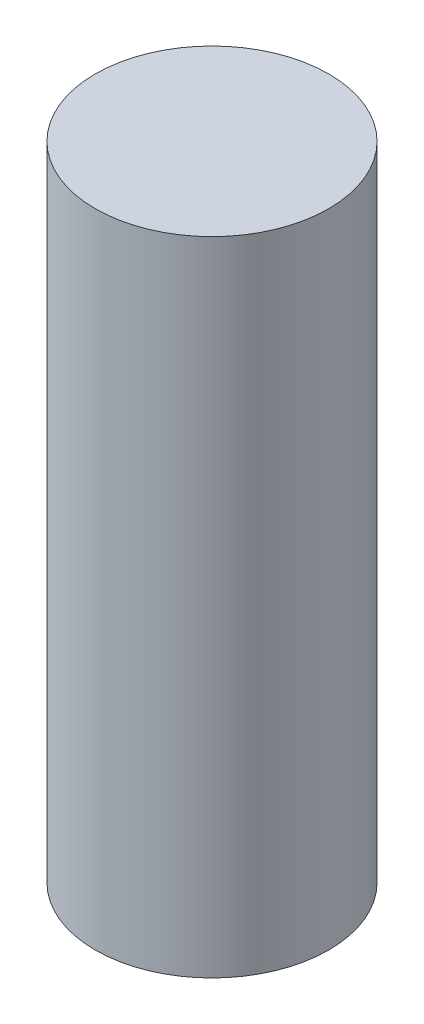
SolidWorks part; units mm, degrees
material "AISI 304"
ref_plane "Front Plane" through (0, 0, 0) normal (0, 0, 1) x (1, 0, 0)
ref_plane "Top Plane" through (0, 0, 0) normal (0, 1, 0) x (1, 0, 0)
ref_plane "Right Plane" through (0, 0, 0) normal (1, 0, 0) x (0, 0, -1)
sketch "Sketch1" plane through (0, 0, 0) normal (0, 1, 0) x (1, 0, 0)
  circle A0 centre (0, 0) radius 30
  dimension "D1" = 60
extrude "Boss-Extrude1" add sketch "Sketch1" along normal blind 165
sketch "Sketch2" plane through (0, 165, 0) normal (0, 1, 0) x (1, 0, 0)
  point P0 (0, 0)
